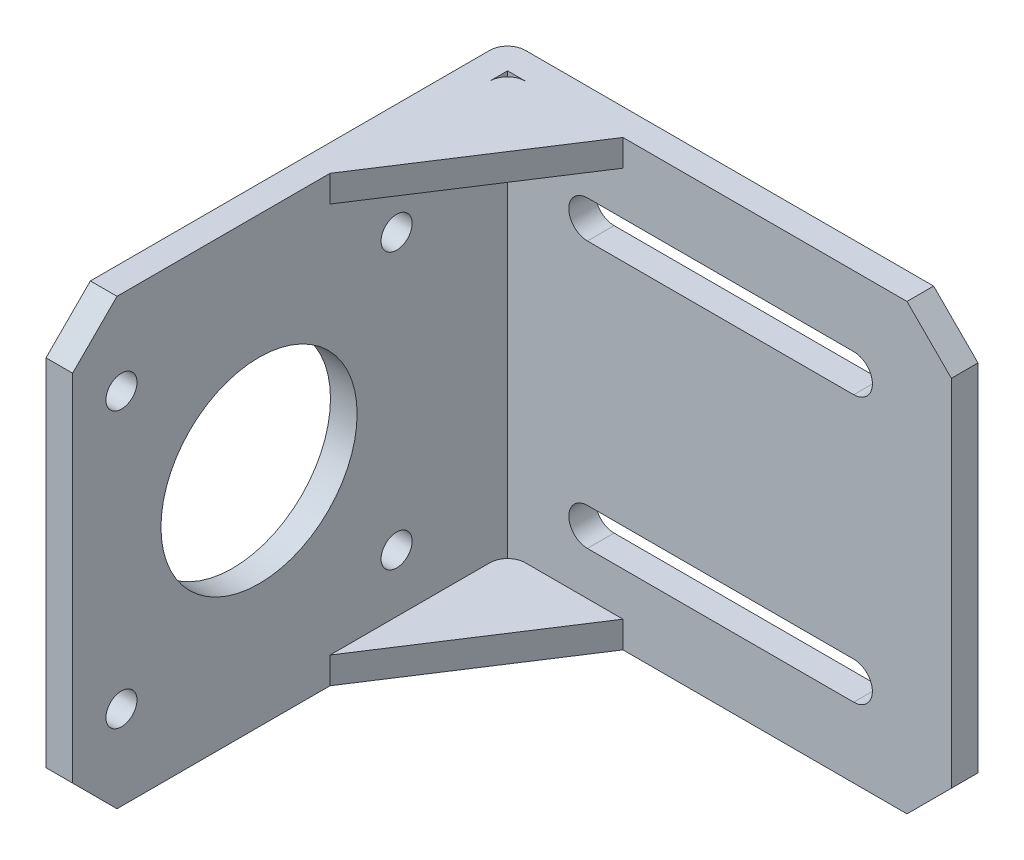
SolidWorks part; units mm, degrees
ref_plane "前视基准面" through (0, 0, 0) normal (0, 0, 1) x (1, 0, 0)
ref_plane "上视基准面" through (0, 0, 0) normal (0, 1, 0) x (1, 0, 0)
ref_plane "右视基准面" through (0, 0, 0) normal (1, 0, 0) x (0, 0, -1)
sketch "草图1" plane through (0, 0, 0) normal (0, 0, 1) x (1, 0, 0)
  line L0 (-14.5, 15) -> (15.5, 15) construction
  line L1 (26.5, -25) -> (-26.5, -25)
  line L2 (26.5, -25) -> (26.5, 25)
  line L3 (26.5, 25) -> (-26.5, 25)
  line L4 (-26.5, -25) -> (-26.5, 25)
  line L5 (26.5, -25) -> (-26.5, 25) construction
  line L6 (26.5, 25) -> (-26.5, -25) construction
  line L7 (-14.5, 17.1033) -> (15.5, 17.1033)
  line L8 (-14.5, 12.8967) -> (15.5, 12.8967)
  line L9 (-14.5, -15) -> (15.5, -15) construction
  line L10 (-14.5, -12.9) -> (15.5, -12.9)
  line L11 (-14.5, -17.1) -> (15.5, -17.1)
  arc A0 (-14.5, 17.1033) -> (-14.5, 12.8967) centre (-14.5, 15) ccw
  arc A1 (15.5, 12.8967) -> (15.5, 17.1033) centre (15.5, 15) ccw
  arc A2 (-14.5, -12.9) -> (-14.5, -17.1) centre (-14.5, -15) ccw
  arc A3 (15.5, -17.1) -> (15.5, -12.9) centre (15.5, -15) ccw
  point P0 (0, 0)
  point P8 (0.5, 15)
  point P14 (0.5, -15)
  dimension "D7" = 2.1033
  dimension "D8" = 2.1
  dimension "D1" = 50
  dimension "D2" = 53
  dimension "D3" = 30
  dimension "D4" = 30
  dimension "D5" = 30
  dimension "D6" = 15
  dimension "D9" = 11
  dimension "D10" = 11
extrude "凸台-拉伸1" add sketch "草图1" along normal blind 3
sketch "草图2" plane through (-26.5, 0, 0) normal (-1, 0, 0) x (0, 0, 1)
  line L0 (3, 25) -> (52, 25)
  line L1 (52, 25) -> (52, -25)
  line L2 (52, -25) -> (3, -25)
  line L4 (3, 25) -> (3, -25)
  line L6 (46.5, 15.5) -> (15.5, 15.5) construction
  line L7 (46.5, 15.5) -> (46.5, -15.5) construction
  line L8 (46.5, -15.5) -> (15.5, -15.5) construction
  line L9 (15.5, 15.5) -> (15.5, -15.5) construction
  line L10 (46.5, 15.5) -> (15.5, -15.5) construction
  line L11 (46.5, -15.5) -> (15.5, 15.5) construction
  circle A0 centre (31, 0) radius 11.05
  circle A5 centre (46.5, 15.5) radius 1.75
  circle A6 centre (46.5, -15.5) radius 1.75
  circle A7 centre (15.5, -15.5) radius 1.75
  circle A8 centre (15.5, 15.5) radius 1.75
  dimension "D1" = 21
  dimension "D2" = 22.1
  dimension "D3" = 49
  dimension "D13" = 25
extrude "凸台-拉伸2" add sketch "草图2" against normal blind 3
chamfer "倒角1" distance 5 angle 45 4 edges at (26.5, -25, 1.5) (26.5, 25, 1.5) (-25, -25, 52) (-25, 25, 52)
sketch "草图3" plane through (0, -25, 0) normal (0, -1, 0) x (1, 0, 0)
  line L0 (-23.5, 5) -> (-23.5, 23)
  line L1 (-23.5, 3) -> (-23.5, 47) construction
  line L2 (-21.5, 3) -> (-10.5, 3)
  line L3 (-23.5, 3) -> (21.5, 3) construction
  line L4 (-10.5, 3) -> (-23.5, 23)
  arc A0 (-23.5, 5) -> (-21.5, 3) centre (-21.5, 5) ccw
extrude "凸台-拉伸3" add sketch "草图3" against normal blind 3
fillet "圆角1" radius 2 1 edges at (-26.5, 0, 0)
mirror "镜向1" about plane through (0, 0, 0) normal (0, 1, 0) of "凸台-拉伸3"
